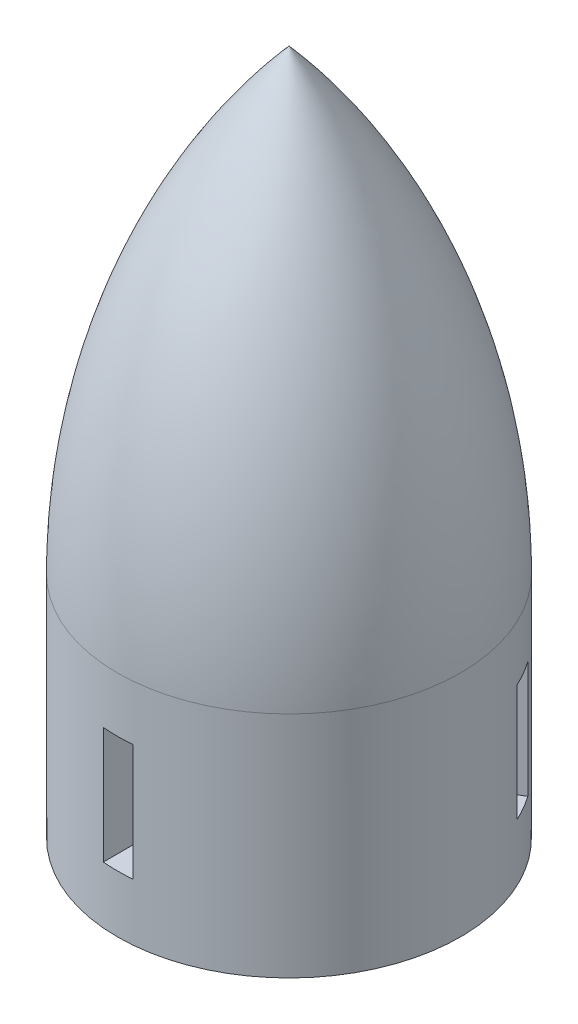
SolidWorks part; units mm, degrees
ref_plane "Front Plane" through (0, 0, 0) normal (0, 0, 1) x (1, 0, 0)
ref_plane "Top Plane" through (0, 0, 0) normal (0, 1, 0) x (1, 0, 0)
ref_plane "Right Plane" through (0, 0, 0) normal (1, 0, 0) x (0, 0, -1)
sketch "Sketch1" plane through (0, 0, 0) normal (0, 1, 0) x (1, 0, 0)
  circle A0 centre (0, 0) radius 19.05
  dimension "D1" = 38.1
extrude "Boss-Extrude1" add sketch "Sketch1" along normal blind 25.4
sketch "Sketch2" plane through (0, 0, 0) normal (0, -1, 0) x (1, 0, 0)
  line L12 (-1.27, 1.9629) -> (-1.27, 3.683)
  line L13 (-1.27, 3.683) -> (1.27, 3.683)
  line L14 (1.27, 3.683) -> (1.27, 1.9629)
  line L15 (1.27, 1.9629) -> (1.9629, 1.27)
  line L16 (1.9629, 1.27) -> (3.683, 1.27)
  line L17 (3.683, 1.27) -> (3.683, -1.27)
  line L18 (3.683, -1.27) -> (1.9629, -1.27)
  line L19 (1.9629, -1.27) -> (1.27, -1.9629)
  line L20 (1.27, -1.9629) -> (1.27, -3.683)
  line L21 (1.27, -3.683) -> (-1.27, -3.683)
  line L22 (-1.27, -3.683) -> (-1.27, -1.9629)
  line L23 (-1.27, -1.9629) -> (-1.9629, -1.27)
  line L24 (-1.9629, -1.27) -> (-3.683, -1.27)
  line L25 (-3.683, -1.27) -> (-3.683, 1.27)
  line L26 (-3.683, 1.27) -> (-1.9629, 1.27)
  line L27 (-1.9629, 1.27) -> (-1.27, 1.9629)
  line L28 (0, 3.683) -> (0, -3.683) construction
  line L29 (-3.683, 0) -> (3.683, 0) construction
  point P16 (0, 3.683)
  point P18 (0, -3.683)
  point P20 (1.27, 2.4793)
  point P21 (3.683, 0)
  point P22 (-3.683, 0)
  dimension "D1" = 2.54
  dimension "D2" = 7.366
  dimension "D3" = 4.572
extrude "Cut-Extrude1" cut sketch "Sketch2" against normal blind 12.7
sketch "Sketch3" plane through (0, 0, 0) normal (0, 0, 1) x (1, 0, 0)
  line L1 (0, 76.2) -> (0, 25.4)
  line L2 (19.05, 25.4) -> (-19.05, 25.4) construction
  line L3 (0, 25.4) -> (19.05, 25.4)
  line L4 (19.05, 0) -> (19.05, 25.4) construction
  arc A0 (19.05, 25.4) -> (0, 76.2) centre (-58.2083, 25.4) ccw
  point P3 (-6.5575, 75.9173)
  dimension "D1" = 76.2
revolve "Revolve1" add sketch "Sketch3" angle 360 about L1
ref_plane "Plane1" through (0, 0, 19.05) normal (0, 0, 1) x (1, 0, 0)
sketch "Sketch4" plane through (0, 0, 19.05) normal (0, 0, 1) x (1, 0, 0)
  line L0 (-19.05, 0) -> (19.05, 0) construction
  line L1 (-1.651, 19.304) -> (1.651, 19.304)
  line L2 (-1.651, 19.304) -> (-1.651, 6.35)
  line L3 (-1.651, 6.35) -> (1.651, 6.35)
  line L4 (1.651, 19.304) -> (1.651, 6.35)
  point P4 (0, 6.35)
  dimension "D1" = 3.302
  dimension "D2" = 12.954
  dimension "D3" = 6.35
extrude "Cut-Extrude2" cut sketch "Sketch4" against normal blind 6.35
pattern_circular "CirPattern1" count 3 over 360 about axis through (0, 0, 0) along (0, 1, 0) of "Cut-Extrude2"
